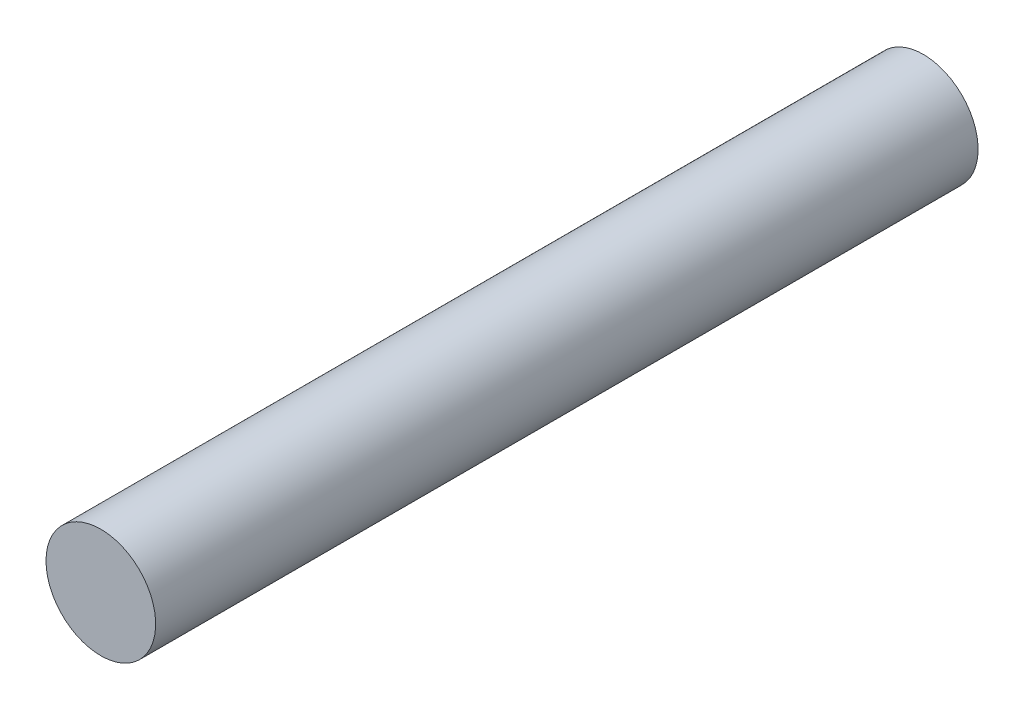
SolidWorks part; units mm, degrees
material "PVC Rigid"
ref_plane "Front Plane" through (0, 0, 0) normal (0, 0, 1) x (1, 0, 0)
ref_plane "Top Plane" through (0, 0, 0) normal (0, 1, 0) x (1, 0, 0)
ref_plane "Right Plane" through (0, 0, 0) normal (1, 0, 0) x (0, 0, -1)
sketch "Sketch1" plane through (0, 0, 0) normal (0, 0, 1) x (1, 0, 0)
  circle A0 centre (0, 0) radius 6
extrude "Boss-Extrude1" add sketch "Sketch1" along normal blind 90
